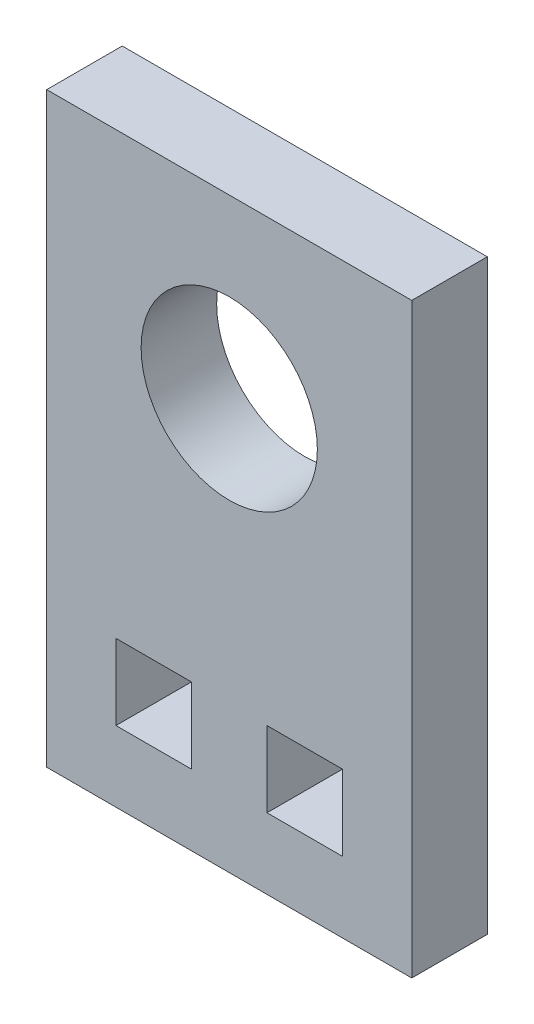
SolidWorks part; units mm, degrees
ref_plane "Front Plane" through (0, 0, 0) normal (0, 0, 1) x (1, 0, 0)
ref_plane "Top Plane" through (0, 0, 0) normal (0, 1, 0) x (1, 0, 0)
ref_plane "Right Plane" through (0, 0, 0) normal (1, 0, 0) x (0, 0, -1)
sketch "Sketch1" plane through (0, 0, 0) normal (0, 0, 1) x (1, 0, 0)
  line L0 (0.0436, 13.3694) -> (0.0436, -7.1259) construction
  line L1 (-7.2064, -7.1306) -> (-7.2064, 13.3694)
  line L2 (-7.2064, 13.3694) -> (7.2936, 13.3694)
  line L3 (7.2936, -6.9397) -> (7.2936, 13.3694)
  line L4 (-7.2064, -7.1306) -> (7.2936, 13.3694) construction
  line L5 (-7.2064, 13.3694) -> (7.2936, -6.9397) construction
  line L6 (-4.4564, -7.1306) -> (-4.4564, -4.1306)
  line L7 (-4.4564, -4.1306) -> (-1.4564, -4.1306)
  line L8 (-1.4564, -7.1306) -> (-1.4564, -4.1306)
  line L9 (4.5436, -4.1306) -> (1.5436, -4.1306)
  line L10 (1.5436, -7.1306) -> (1.5436, -4.1306)
  line L11 (4.5436, -7.1306) -> (4.5436, -4.1306)
  line L12 (1.5436, -7.1306) -> (4.5436, -7.1306)
  line L13 (-4.4564, -7.1306) -> (-1.4564, -7.1306)
  line L14 (-7.2064, -7.1306) -> (-7.2064, -9.9397)
  line L15 (-7.2064, -9.9397) -> (7.2936, -9.9397)
  line L16 (7.2936, -6.9397) -> (7.2936, -9.9397)
  circle A0 centre (0.0436, 6.3694) radius 3.5
  point P0 (0.0775, 3.1674)
  dimension "D1" = 20.5
  dimension "D2" = 3
  dimension "D3" = 3
  dimension "D4" = 1.5
  dimension "D5" = 3
  dimension "D6" = 3
  dimension "D7" = 14.5
  dimension "D8" = 0
  dimension "D9" = 7
extrude "Boss-Extrude1" add sketch "Sketch1" along normal blind 3
